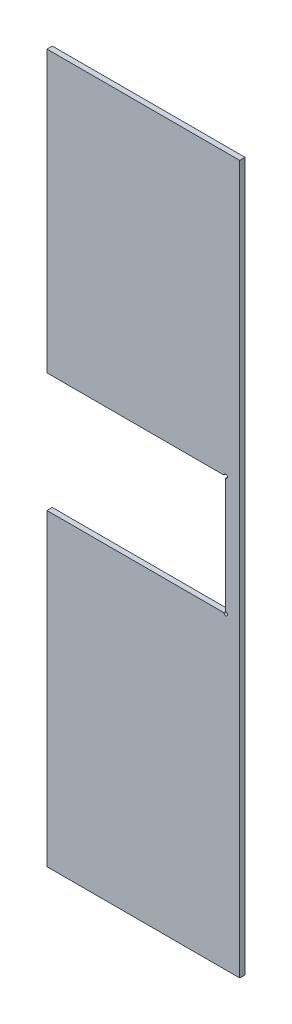
SolidWorks part; units mm, degrees
ref_plane "Front Plane" through (0, 0, 0) normal (0, 0, 1) x (1, 0, 0)
ref_plane "Top Plane" through (0, 0, 0) normal (0, 1, 0) x (1, 0, 0)
ref_plane "Right Plane" through (0, 0, 0) normal (1, 0, 0) x (0, 0, -1)
sketch "Sketch1" plane through (0, 0, 0) normal (0, 0, 1) x (1, 0, 0)
  line L0 (-13.75, -6.5) -> (11.75, -6.5)
  line L1 (-13.75, -50.5) -> (13.75, -50.5)
  line L2 (-13.75, -50.5) -> (-13.75, -6.5)
  line L3 (-13.75, 50.5) -> (13.75, 50.5)
  line L4 (13.75, -50.5) -> (13.75, 50.5)
  line L5 (-13.75, -50.5) -> (13.75, 50.5) construction
  line L6 (-13.75, 50.5) -> (13.75, -50.5) construction
  line L7 (11.75, -6.5) -> (11.75, 10.5)
  line L8 (11.75, 10.5) -> (-13.75, 10.5)
  line L9 (-13.75, 10.5) -> (-13.75, 50.5)
  point P0 (0, 0)
  dimension "D1" = 27.5
  dimension "D2" = 101
  dimension "D3" = 17
  dimension "D4" = 44
  dimension "D5" = 2
extrude "Boss-Extrude1" add sketch "Sketch1" along normal blind 0.76
sketch "Sketch2" plane through (0, 0, 0.76) normal (0, 0, 1) x (1, 0, 0)
  circle A0 centre (11.75, 10.5) radius 0.25
  circle A1 centre (11.75, -6.5) radius 0.25
  dimension "D1" = 0.5
  dimension "D2" = 0.5
extrude "Cut-Extrude1" cut sketch "Sketch2" against normal blind 10
